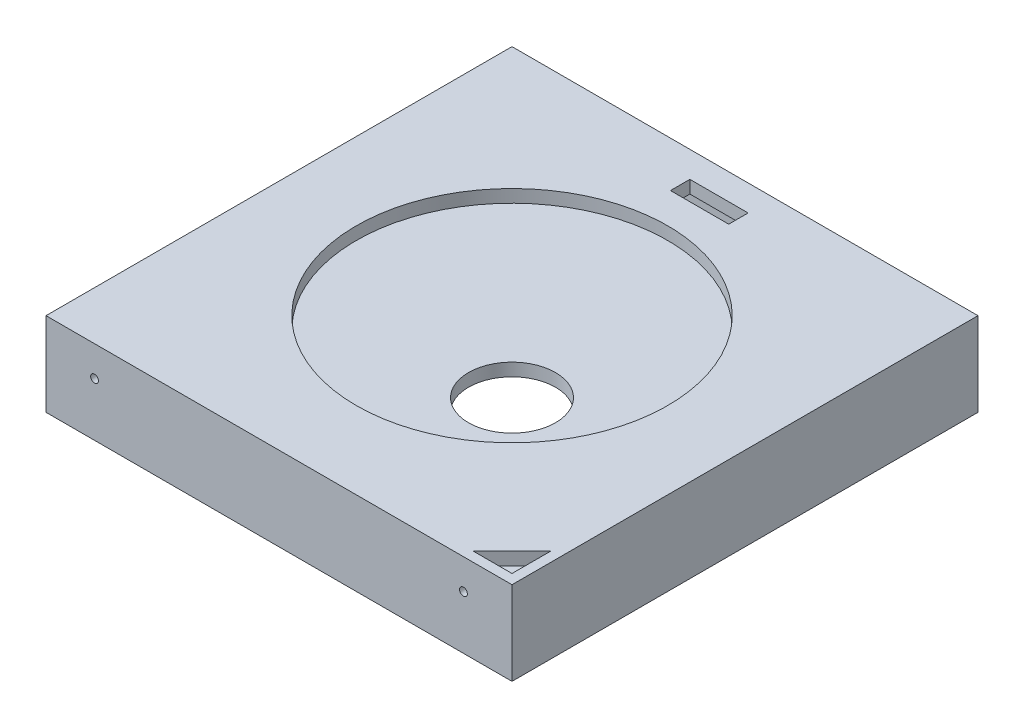
SolidWorks part; units mm, degrees
ref_plane "Front Plane" through (0, 0, 0) normal (0, 0, 1) x (1, 0, 0)
ref_plane "Top Plane" through (0, 0, 0) normal (0, 1, 0) x (1, 0, 0)
ref_plane "Right Plane" through (0, 0, 0) normal (1, 0, 0) x (0, 0, -1)
sketch "Sketch1" plane through (0, 0, 0) normal (0, 1, 0) x (1, 0, 0)
  line L1 (-138.6625, 95.3037) -> (166.1375, 95.3037)
  line L2 (-138.6625, 95.3037) -> (-138.6625, -209.4963)
  line L3 (-138.6625, -209.4963) -> (166.1375, -209.4963)
  line L4 (166.1375, 95.3037) -> (166.1375, -209.4963)
  dimension "D1" = 304.8
  dimension "D2" = 304.8
extrude "Boss-Extrude1" add sketch "Sketch1" along normal blind 54.77
sketch "Sketch2" plane through (0, 54.77, 0) normal (0, 1, 0) x (1, 0, 0)
  line L0 (134.3875, -203.1463) -> (159.7875, -203.1463)
  line L5 (-5.3125, 78.2914) -> (32.7875, 78.2914)
  line L6 (-5.3125, 78.2914) -> (-5.3125, 65.5914)
  line L7 (-5.3125, 65.5914) -> (32.7875, 65.5914)
  line L8 (32.7875, 78.2914) -> (32.7875, 65.5914)
  line L9 (159.7875, -203.1463) -> (159.7875, -177.7463)
  line L10 (166.1375, -209.4963) -> (166.1375, 95.3037) construction
  line L11 (159.7875, -177.7463) -> (134.3875, -203.1463)
  line L12 (166.1375, 95.3037) -> (-138.6625, 95.3037) construction
  line L13 (-138.6625, -209.4963) -> (166.1375, -209.4963) construction
  circle A0 centre (13.7375, -57.0963) radius 101.854
  dimension "D1" = 203.708
  dimension "D6" = 25.4
  dimension "D2" = 152.4
  dimension "D3" = 152.4
  dimension "D4" = 6.35
  dimension "D5" = 6.35
  dimension "D7" = 25.4
  dimension "D8" = 38.1
  dimension "D9" = 12.7
  dimension "D10" = 19.05
extrude "Cut-Extrude3" cut sketch "Sketch2" against normal blind 38.1
sketch "Sketch3" plane through (0, 0, 209.4963) normal (0, 0, 1) x (1, 0, 0)
  line L2 (166.1375, 54.77) -> (166.1375, 0) construction
  line L3 (-138.6625, 54.77) -> (166.1375, 54.77) construction
  line L4 (-138.6625, 54.77) -> (-138.6625, 0) construction
  circle A0 centre (134.3875, 34.958) radius 2.54
  circle A1 centre (-106.9125, 34.958) radius 2.54
  dimension "D1" = 5.08
  dimension "D4" = 5.08
  dimension "D2" = 31.75
  dimension "D3" = 19.812
  dimension "D5" = 31.75
  dimension "D6" = 19.812
extrude "Cut-Extrude4" cut sketch "Sketch3" against normal blind 31.75
ref_plane "Plane1" through (0, 27.385, 0) normal (0, 1, 0) x (1, 0, 0)
sketch "Sketch4" plane through (0, 27.385, 0) normal (0, 1, 0) x (1, 0, 0)
  line L0 (-138.6625, 95.3037) -> (-138.6625, -209.4963) construction
  line L1 (-132.3125, 88.9537) -> (159.7875, 88.9537)
  line L2 (-132.3125, 88.9537) -> (-132.3125, -203.1463)
  line L3 (-132.3125, -203.1463) -> (159.7875, -203.1463)
  line L4 (159.7875, 88.9537) -> (159.7875, -203.1463)
  line L5 (166.1375, 95.3037) -> (-138.6625, 95.3037) construction
  line L6 (166.1375, -209.4963) -> (166.1375, 95.3037) construction
  line L7 (-138.6625, -209.4963) -> (166.1375, -209.4963) construction
  dimension "D1" = 6.35
  dimension "D2" = 6.35
  dimension "D3" = 6.35
  dimension "D4" = 6.35
extrude "Cut-Extrude5" cut sketch "Sketch4" against normal blind 19.05 and the other way blind 19.05
sketch "Sketch5" plane through (0, 0, 0) normal (0, -1, 0) x (1, 0, 0)
  line L0 (166.1375, 209.4963) -> (166.1375, -95.3037) construction
  line L1 (-138.6625, 209.4963) -> (166.1375, 209.4963) construction
  circle A0 centre (13.7375, 57.0963) radius 28.448
  dimension "D3" = 56.896
  dimension "D1" = 152.4
  dimension "D2" = 152.4
extrude "Cut-Extrude6" cut sketch "Sketch5" against normal through all
